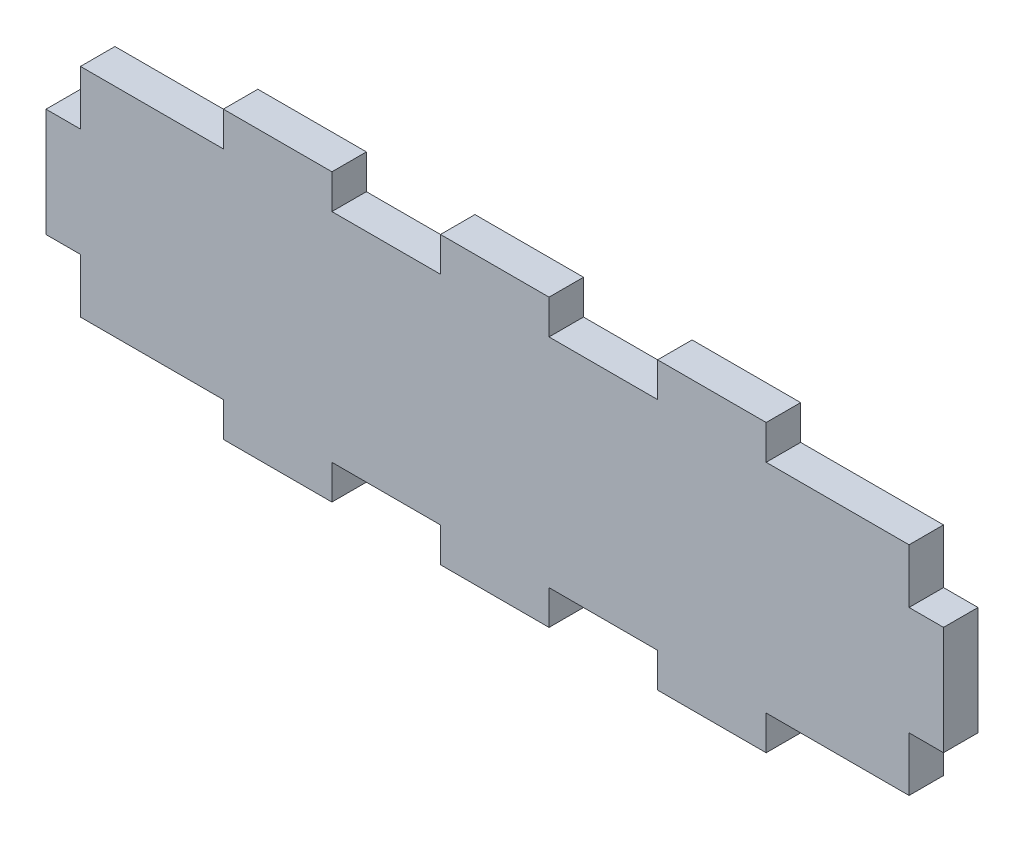
SolidWorks part; units mm, degrees
ref_plane "Plan de face" through (0, 0, 0) normal (0, 0, 1) x (1, 0, 0)
ref_plane "Plan de dessus" through (0, 0, 0) normal (0, 1, 0) x (1, 0, 0)
ref_plane "Plan de droite" through (0, 0, 0) normal (1, 0, 0) x (0, 0, -1)
sketch "Esquisse1" plane through (0, 0, 0) normal (0, 0, 1) x (1, 0, 0)
  line L1 (-82.675, 26.35) -> (82.675, 26.35)
  line L2 (-82.675, 26.35) -> (-82.675, -26.35)
  line L3 (-82.675, -26.35) -> (82.675, -26.35)
  line L4 (82.675, 26.35) -> (82.675, -26.35)
  point P4 (0, -26.35)
  point P6 (82.675, 0)
  dimension "D1" = 165.35
  dimension "D2" = 52.7
extrude "Boss.-Extru.1" add sketch "Esquisse1" along normal blind 6.35
sketch "Esquisse2" plane through (0, 0, 6.35) normal (0, 0, 1) x (1, 0, 0)
  line L0 (-82.675, 26.35) -> (-82.675, -26.35) construction
  line L11 (-82.675, 10) -> (-76.325, 10)
  line L12 (-82.675, 10) -> (-82.675, -10)
  line L13 (-82.675, -10) -> (-76.325, -10)
  line L14 (-76.325, 10) -> (-76.325, -10)
  point P6 (-76.325, 0)
  dimension "D3" = 20
  dimension "D4" = 6.35
sketch "Esquisse3" plane through (0, 0, 6.35) normal (0, 0, 1) x (1, 0, 0)
  line L16 (-82.675, -10) -> (-76.325, -10) construction
  line L17 (-82.675, -10) -> (-76.325, -10)
  line L18 (-82.675, -10) -> (-82.675, -26.35)
  line L19 (-82.675, -26.35) -> (-76.325, -26.35)
  line L20 (-76.325, -10) -> (-76.325, -26.35)
  line L21 (-82.675, -26.35) -> (82.675, -26.35) construction
  line L22 (-82.675, 26.35) -> (-82.675, -26.35) construction
  line L23 (-76.325, 10) -> (-76.325, -10) construction
  line L25 (-82.675, 26.35) -> (-76.325, 26.35)
  line L26 (-82.675, 26.35) -> (-82.675, 10)
  line L27 (-82.675, 10) -> (-76.325, 10)
  line L28 (-76.325, 26.35) -> (-76.325, 10)
extrude "Enlèv. mat.-Extru.1" cut sketch "Esquisse3" against normal through all
mirror "Symétrie1" about plane through (0, 0, 0) normal (1, 0, 0) of "Enlèv. mat.-Extru.1"
sketch "Esquisse4" plane through (0, 0, 6.35) normal (0, 0, 1) x (1, 0, 0)
  line L0 (-76.325, -26.35) -> (76.325, -26.35) construction
  line L1 (-50, -26.35) -> (-30, -26.35)
  line L2 (-50, -26.35) -> (-50, -20)
  line L3 (-50, -20) -> (-30, -20)
  line L4 (-30, -26.35) -> (-30, -20)
  line L6 (-10, -26.35) -> (10, -26.35)
  line L7 (-10, -26.35) -> (-10, -20)
  line L8 (-10, -20) -> (10, -20)
  line L9 (10, -26.35) -> (10, -20)
  line L10 (30, -26.35) -> (50, -26.35)
  line L11 (30, -26.35) -> (30, -20)
  line L12 (30, -20) -> (50, -20)
  line L13 (50, -26.35) -> (50, -20)
  point P14 (0, -20)
  dimension "D1" = 6.35
  dimension "D2" = 20
  dimension "D3" = 20
  dimension "D4" = 20
sketch "Esquisse5" plane through (0, 0, 6.35) normal (0, 0, 1) x (1, 0, 0)
  line L0 (76.325, -26.35) -> (76.325, -10) construction
  line L1 (-30, -26.35) -> (-10, -26.35)
  line L2 (-30, -26.35) -> (-30, -20)
  line L3 (-30, -20) -> (-10, -20)
  line L4 (-10, -26.35) -> (-10, -20)
  line L5 (10, -26.35) -> (30, -26.35)
  line L6 (10, -26.35) -> (10, -20)
  line L7 (10, -20) -> (30, -20)
  line L8 (30, -26.35) -> (30, -20)
  line L9 (50, -26.35) -> (76.325, -26.35)
  line L10 (50, -26.35) -> (50, -20)
  line L11 (50, -20) -> (76.325, -20)
  line L12 (76.325, -26.35) -> (76.325, -20)
  line L13 (-76.325, -26.35) -> (-76.325, -10) construction
  line L14 (-50, -26.35) -> (-76.325, -26.35)
  line L15 (-50, -26.35) -> (-50, -20)
  line L16 (-50, -20) -> (-76.325, -20)
  line L17 (-76.325, -26.35) -> (-76.325, -20)
  line L18 (-50, -20) -> (-30, -20) construction
  line L19 (30, -20) -> (50, -20) construction
extrude "Enlèv. mat.-Extru.2" cut sketch "Esquisse5" against normal through all
mirror "Symétrie2" about plane through (0, 0, 0) normal (0, 1, 0) of "Enlèv. mat.-Extru.2"
